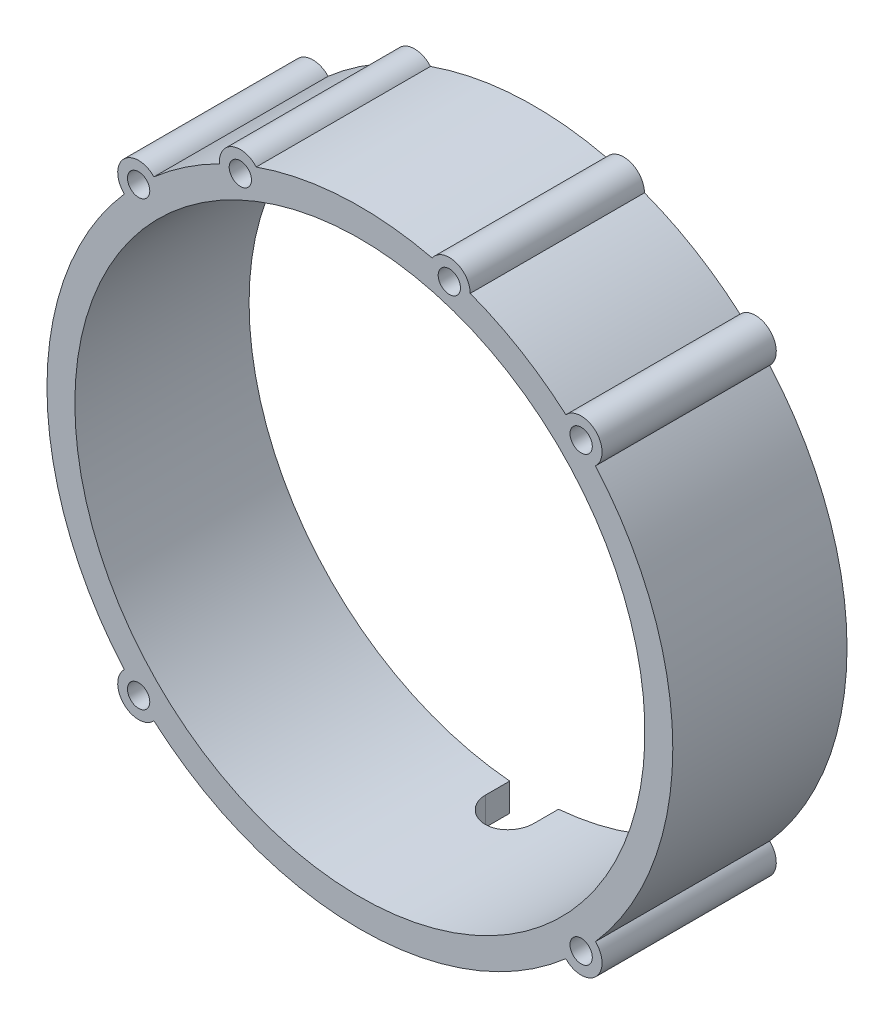
SolidWorks part; units mm, degrees
material "ABS"
ref_plane "前视基准面" through (0, 0, 0) normal (0, 0, 1) x (1, 0, 0)
ref_plane "上视基准面" through (0, 0, 0) normal (0, 1, 0) x (1, 0, 0)
ref_plane "右视基准面" through (0, 0, 0) normal (1, 0, 0) x (0, 0, -1)
sketch "草图1" plane through (0, 0, 0) normal (0, 0, 1) x (1, 0, 0)
  line L0 (-9.35, 50.0979) -> (9.35, 50.0979) construction
  line L1 (0, 50.0979) -> (0, 0) construction
  line L2 (-9.35, 50.0979) -> (-10.85, 50.0979) construction
  line L3 (9.35, 50.0979) -> (11.35, 50.0979) construction
  line L4 (0, 0) -> (12.8351, 41.9818) construction
  arc A0 (-17.6706, 36.8858) -> (7.8297, 40.1436) centre (0, 0) ccw
  arc A1 (-17.6706, 36.8858) -> (-9.35, 50.0979) centre (-24, 50.0979) ccw construction
  arc A2 (7.8297, 40.1436) -> (9.35, 50.0979) centre (-24, 50.0979) ccw construction
  arc A3 (-30.6806, 27.0465) -> (0, 50.0979) centre (-24, 50.0979) ccw construction
  arc A7 (11.1055, 45.9474) -> (11.35, 50.0979) centre (-24, 50.0979) ccw construction
  circle A8 centre (0, 0) radius 34 construction
  arc A15 (11.8433, 44.8631) -> (15.0201, 43.9017) centre (0, 0) cw construction
  arc A17 (15.6798, 42.774) -> (15.1953, 40.514) centre (-24, 50.0979) cw construction
  circle A18 centre (0, 0) radius 43.9 construction
  circle A19 centre (12.8351, 41.9818) radius 1.6
  circle A20 centre (36.8176, 23.9097) radius 1.6 construction
  circle A21 centre (43.5728, -5.3501) radius 1.6 construction
  circle A22 centre (29.9397, -32.1064) radius 1.6 construction
  circle A23 centre (2.2975, -43.8398) radius 1.6 construction
  circle A24 centre (-26.4197, -35.0601) radius 1.6 construction
  circle A25 centre (-42.7748, -9.8754) radius 1.6 construction
  circle A26 centre (-39.1152, 19.9302) radius 1.6 construction
  circle A27 centre (-17.1531, 40.4102) radius 1.6
  arc A29 (-13.3104, 42.4393) -> (-10.85, 50.0979) centre (-24, 50.0979) ccw construction
  arc A30 (-14.8807, 42.3688) -> (-13.3104, 42.4393) centre (-14.1233, 43.0217) ccw construction
  arc A32 (15.7942, 39.3485) -> (15.1953, 40.514) centre (16.1667, 40.2765) cw construction
  arc A33 (15.0201, 43.9017) -> (15.6798, 42.774) centre (14.6964, 42.9555) cw construction
  arc A34 (11.8433, 44.8631) -> (11.1055, 45.9474) centre (12.0986, 45.83) cw construction
  arc A35 (-17.6706, 36.8858) -> (7.8297, 40.1436) centre (0, 0) cw
  circle A43 centre (0, 0) radius 46.9
  point P39 (0, 0)
  dimension "D1" = 81.8
  dimension "D3" = 24
  dimension "D4" = 6
  dimension "D5" = 2
  dimension "D6" = 68
  dimension "D7" = 3
  dimension "D8" = 5.5
  dimension "D9" = 5
  dimension "D10" = 9
  dimension "D11" = 17
  dimension "D13" = 3.2
  dimension "D15" = 1
  dimension "D16" = 1
  dimension "D2" = 9.35
  dimension "D14" = 9.35
extrude "凸台-拉伸1" add sketch "草图1" along normal blind 25
sketch "草图2" plane through (0, 0, 25) normal (0, 0, 1) x (1, 0, 0)
  circle A0 centre (0, 0) radius 44.9 construction
  circle A1 centre (-31.7491, 31.7491) radius 3
  circle A2 centre (31.7491, 31.7491) radius 3
  circle A3 centre (31.7491, -31.7491) radius 3
  circle A4 centre (-31.7491, -31.7491) radius 3
  point P15 (0, 0)
  dimension "D2" = 6
  dimension "D3" = 89.8
  dimension "D1" = 4
extrude "凸台-拉伸2" add sketch "草图2" against normal up to surface (25 mm away) up to face at (46.9, 0, 0)
sketch "草图3" plane through (0, 0, 25) normal (0, 0, 1) x (1, 0, 0)
  circle A0 centre (-31.7491, 31.7491) radius 1.6
  circle A1 centre (-31.7491, -31.7491) radius 1.6
  circle A2 centre (31.7491, -31.7491) radius 1.6
  circle A3 centre (31.7491, 31.7491) radius 1.6
  dimension "D1" = 3.2
extrude "切除-拉伸1" cut sketch "草图3" against normal through all
sketch "草图4" plane through (0, 0, 25) normal (0, 0, 1) x (1, 0, 0)
  line L0 (0, 0) -> (0, 46.9) construction
  arc A0 (-34.7394, 31.5084) -> (-33.7984, 29.5581) centre (-31.7491, 31.7491) ccw
  arc A1 (-34.7394, -31.5084) -> (-33.7984, -29.5581) centre (-31.7491, -31.7491) cw
  arc A2 (-31.5084, -34.7394) -> (-29.5581, -33.7984) centre (-31.7491, -31.7491) ccw
  arc A3 (-20.14, 40.1297) -> (-14.8765, 42.3639) centre (-17.1531, 40.4102) cw
  arc A5 (31.5084, 34.7394) -> (-31.5084, 34.7394) centre (0, 0) ccw construction
  arc A6 (-31.5084, 34.7394) -> (-29.5581, 33.7984) centre (-31.7491, 31.7491) cw
  arc A8 (-33.7984, 29.5581) -> (-33.7984, -29.5581) centre (0, 0) ccw
  arc A9 (-31.5084, -34.7394) -> (31.5084, -34.7394) centre (0, 0) ccw construction
  arc A11 (-34.7394, 31.5084) -> (-34.7394, -31.5084) centre (0, 0) ccw construction
  arc A12 (-31.5084, -34.7394) -> (31.5084, -34.7394) centre (0, 0) ccw
  arc A14 (31.5084, 34.7394) -> (-31.5084, 34.7394) centre (0, 0) ccw
  arc A15 (-34.7394, 31.5084) -> (-34.7394, -31.5084) centre (0, 0) ccw
  arc A16 (-20.14, 40.1297) -> (-29.5581, 33.7984) centre (0, 0) ccw
  arc A17 (-29.5581, -33.7984) -> (29.5581, -33.7984) centre (0, 0) ccw
  arc A18 (34.7394, 31.5084) -> (34.7394, -31.5084) centre (0, 0) cw
  arc A19 (33.7984, 29.5581) -> (33.7984, -29.5581) centre (0, 0) cw
  arc A20 (31.5084, 34.7394) -> (29.5581, 33.7984) centre (31.7491, 31.7491) ccw
  arc A21 (15.8349, 42.0151) -> (10.3668, 43.6868) centre (12.8351, 41.9818) ccw
  arc A22 (31.5084, -34.7394) -> (29.5581, -33.7984) centre (31.7491, -31.7491) cw
  arc A23 (34.7394, -31.5084) -> (33.7984, -29.5581) centre (31.7491, -31.7491) ccw
  arc A24 (34.7394, 31.5084) -> (33.7984, 29.5581) centre (31.7491, 31.7491) cw
  arc A25 (10.3668, 43.6868) -> (-14.8765, 42.3639) centre (0, 0) ccw
  arc A26 (29.5581, 33.7984) -> (15.8349, 42.0151) centre (0, 0) ccw
  arc A27 (33.7984, -29.5581) -> (33.7984, 29.5581) centre (0, 0) ccw
  arc M7 (-34.7394, 31.5084) -> (-34.7394, -31.5084) centre (0, 0) ccw
  arc M9 (-31.5084, -34.7394) -> (31.5084, -34.7394) centre (0, 0) ccw
  arc M11 (34.7394, -31.5084) -> (34.7394, 31.5084) centre (0, 0) ccw
  arc M13 (31.5084, 34.7394) -> (-31.5084, 34.7394) centre (0, 0) ccw
extrude "切除-拉伸2" cut sketch "草图4" against normal through all contours A16 A3 A6 M13 | A25 L0 A3 M13 | A26 A20 A21 M13 | L0 A25 A21 A14 | A24 A19 A23 M11 | A22 A17 A2 M9 | A8 A0 A1 M7
sketch "草图6" plane through (0, 0, 0) normal (0, 1, 0) x (1, 0, 0)
  line L4 (-3.5, -3.5) -> (-3.5, 0)
  line L5 (10.3668, 0) -> (-14.8765, 0) construction
  line L6 (-3.5, 0) -> (3.5, 0)
  line L7 (3.5, 0) -> (3.5, -3.5)
  arc A1 (3.5, -3.5) -> (-3.5, -3.5) centre (0, -3.5) cw
  dimension "D1" = 3.5
extrude "切除-拉伸3" cut sketch "草图6" against normal through all
